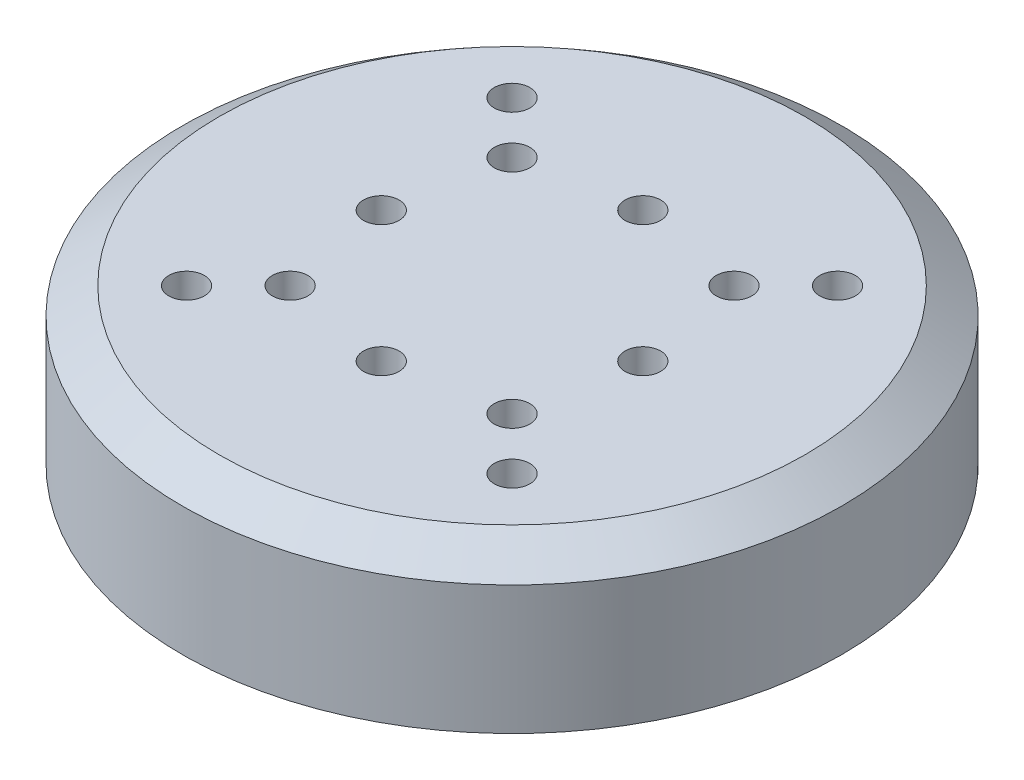
SolidWorks part; units mm, degrees
ref_plane "Front Plane" through (0, 0, 0) normal (0, 0, 1) x (1, 0, 0)
ref_plane "Top Plane" through (0, 0, 0) normal (0, 1, 0) x (1, 0, 0)
ref_plane "Right Plane" through (0, 0, 0) normal (1, 0, 0) x (0, 0, -1)
sketch "Sketch1" plane through (0, 0, 0) normal (0, 0, 1) x (1, 0, 0)
  line L0 (0, -7.4) -> (0, 7.4)
  line L1 (0, 7.4) -> (-28, 7.4)
  line L2 (-28, 7.4) -> (-31.5, 4.9)
  line L3 (-31.5, 4.9) -> (-31.5, -7.4)
  line L4 (-31.5, -7.4) -> (0, -7.4)
  point P4 (0, 0)
  dimension "D1" = 28
  dimension "D2" = 31.5
  dimension "D3" = 2.5
  dimension "D4" = 14.8
revolve "Revolve1" add sketch "Sketch1" angle 360 about L0
sketch "Sketch2" plane through (0, 7.4, 0) normal (0, 1, 0) x (1, 0, 0)
  line L0 (-10.6066, -10.6066) -> (10.6066, 10.6066) construction
  line L1 (10.6066, -10.6066) -> (-10.6066, 10.6066) construction
  line L2 (0, 12.5) -> (0, 0) construction
  circle A0 centre (0, 0) radius 12.5 construction
  circle A1 centre (0, 0) radius 15 construction
  circle A2 centre (0, 0) radius 22 construction
  point P5 (0, 12.5)
  point P6 (-12.5, 0)
  point P7 (0, -12.5)
  point P8 (12.5, 0)
  point P11 (0, 0)
  point P15 (0, 0)
  point P16 (-15.5563, 15.5563)
  point P17 (15.5563, 15.5563)
  point P18 (15.5563, -15.5563)
  point P19 (-15.5563, -15.5563)
  dimension "D1" = 25
  dimension "D2" = 30
  dimension "D3" = 44
  dimension "D4" = 45
hole_wizard "M3 Clearance Hole1" positions "Sketch3" profile "Sketch4" hole size "M3" standard "ANSI Metric"
sketch "Sketch3" plane through (0, 7.4, 0) normal (0, 1, 0) x (1, 0, 0)
  point P0 (-15.5563, 15.5563)
  point P3 (-10.6066, 10.6066)
  point P6 (0, 12.5)
  point P9 (10.6066, 10.6066)
  point P12 (15.5563, 15.5563)
  point P15 (0, -12.5)
  point P18 (-12.5, 0)
  point P21 (12.5, 0)
  point P24 (10.6066, -10.6066)
  point P27 (-10.6066, -10.6066)
  point P30 (-15.5563, -15.5563)
  point P33 (15.5563, -15.5563)
sketch "Sketch4" plane through (-15.5563, 7.4, -15.5563) normal (1, 0, 0) x (0, 0, 1)
  line L0 (0, 0) -> (0, 5.0215)
  line L1 (0, 5.0215) -> (1.7, 4)
  line L2 (1.7, 4) -> (1.7, 0)
  line L5 (1.7, 0) -> (0, 0)
  line L10 (0, 5.0215) -> (-1.7, 4) construction
  line L11 (0, -6.35) -> (0, 107.95) construction
  dimension "Hole Dia." = 3.4
  dimension "Hole Depth" = 4
  dimension "Drill Angle" = 118
sketch "Sketch5" plane through (0, -7.4, 0) normal (0, -1, 0) x (1, 0, 0)
  circle A2 centre (0, 0) radius 29.5
  circle A3 centre (0, 0) radius 29.5
  dimension "D1" = 2
extrude "Cut-Extrude1" cut sketch "Sketch5" against normal blind 1
